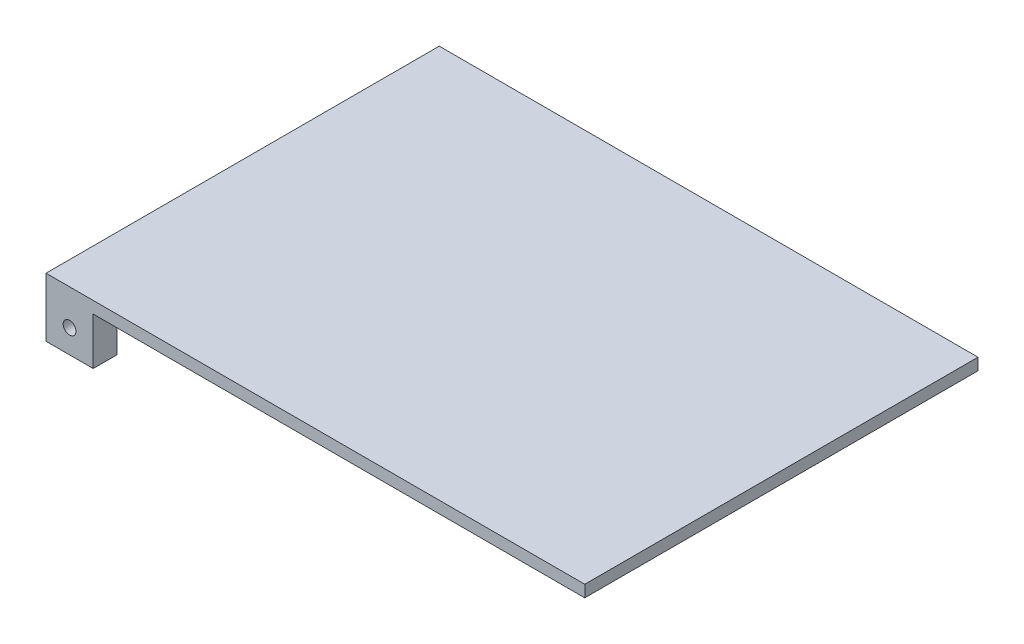
SolidWorks part; units mm, degrees
ref_plane "Front Plane" through (0, 0, 0) normal (0, 0, 1) x (1, 0, 0)
ref_plane "Top Plane" through (0, 0, 0) normal (0, 1, 0) x (1, 0, 0)
ref_plane "Right Plane" through (0, 0, 0) normal (1, 0, 0) x (0, 0, -1)
sketch "Sketch1" plane through (0, 0, 0) normal (0, 1, 0) x (1, 0, 0)
  line L1 (0, 0) -> (150, 0)
  line L2 (0, 0) -> (0, 100)
  line L3 (0, 100) -> (150, 100)
  line L4 (150, 0) -> (150, 100)
  dimension "D1" = 150
  dimension "D2" = 100
extrude "Boss-Extrude1" add sketch "Sketch1" along normal blind 3
sketch "Sketch2" plane through (0, 0, 0) normal (0, -1, 0) x (1, 0, 0)
  line L0 (75, 0) -> (75, -100) construction
  line L1 (0, 0) -> (12, 0)
  line L2 (0, 0) -> (0, -6)
  line L3 (0, -6) -> (12, -6)
  line L4 (12, 0) -> (12, -6)
  line L5 (0, 0) -> (150, 0) construction
  line L6 (150, -100) -> (0, -100) construction
  line L7 (150, -6) -> (138, -6)
  line L8 (138, 0) -> (138, -6)
  line L9 (150, 0) -> (138, 0)
  line L10 (150, 0) -> (150, -6)
  line L11 (0, -50) -> (150, -50) construction
  line L12 (0, -100) -> (0, 0) construction
  line L13 (150, 0) -> (150, -100) construction
  line L14 (150, -100) -> (150, -94)
  line L15 (150, -100) -> (138, -100)
  line L16 (138, -100) -> (138, -94)
  line L17 (150, -94) -> (138, -94)
  line L18 (0, -94) -> (12, -94)
  line L19 (12, -100) -> (12, -94)
  line L20 (0, -100) -> (12, -100)
  line L21 (0, -100) -> (0, -94)
  dimension "D1" = 6
  dimension "D2" = 12
extrude "Boss-Extrude2" add sketch "Sketch2" along normal blind 12
sketch "Sketch4" plane through (0, 0, 0) normal (0, 0, 1) x (1, 0, 0)
  line L0 (12, -12) -> (12, 0) construction
  line L1 (12, -12) -> (0, -12) construction
  line L2 (75, 3) -> (75, 0) construction
  line L3 (0, 3) -> (150, 3) construction
  line L4 (12, 0) -> (138, 0) construction
  circle A0 centre (6, -6) radius 1.625
  circle A1 centre (144, -6) radius 1.625
  dimension "D1" = 3.25
  dimension "D2" = 6
  dimension "D3" = 6
extrude "Cut-Extrude1" cut sketch "Sketch4" against normal through all
sketch "Sketch5" plane through (0, 3, 0) normal (0, 1, 0) x (1, 0, 0)
  line L0 (150, 100) -> (0, 100) construction
  line L1 (150, 0) -> (137, 0)
  line L2 (150, 0) -> (150, 100)
  line L3 (150, 100) -> (137, 100)
  line L4 (137, 0) -> (137, 100)
  dimension "D1" = 13
extrude "Cut-Extrude2" cut sketch "Sketch5" against normal through all
